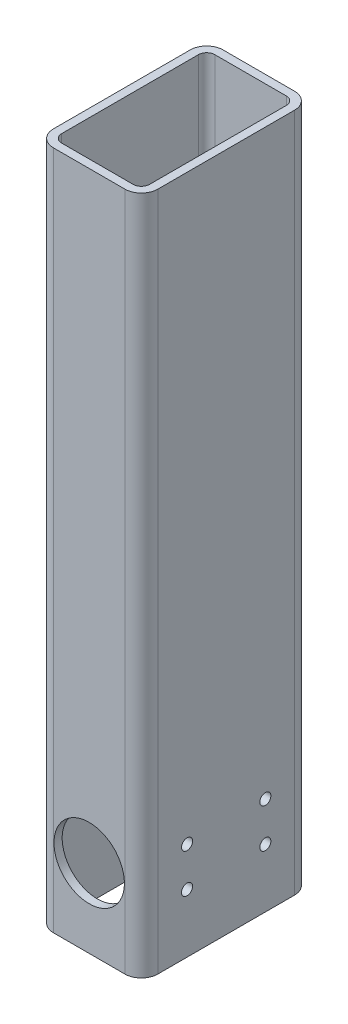
SolidWorks part; units mm, degrees
material "1.0037 (S235JR)"
ref_plane "E_Rechts" through (0, 0, 0) normal (0, 0, 1) x (1, 0, 0)
ref_plane "E_Oben" through (0, 0, 0) normal (0, 1, 0) x (1, 0, 0)
ref_plane "E_Vorne" through (0, 0, 0) normal (1, 0, 0) x (0, 0, -1)
sketch "Skizze1" plane through (0, 0, 0) normal (0, 1, 0) x (1, 0, 0)
  line L0 (-27.4, -58.7) -> (27.4, -58.7)
  line L1 (-33.7, -52.4) -> (-33.7, 52.4)
  line L2 (27.4, 58.7) -> (-27.4, 58.7)
  line L3 (33.7, 52.4) -> (33.7, -52.4)
  line L4 (-27.4, -65) -> (27.4, -65)
  line L5 (-40, -52.4) -> (-40, 52.4)
  line L6 (27.4, 65) -> (-27.4, 65)
  line L7 (40, 52.4) -> (40, -52.4)
  line L8 (-55, 0) -> (55, 0) construction
  line L9 (0, -55) -> (0, 55) construction
  arc A0 (40, 52.4) -> (27.4, 65) centre (27.4, 52.4) ccw
  arc A1 (27.4, -65) -> (40, -52.4) centre (27.4, -52.4) ccw
  arc A2 (-40, -52.4) -> (-27.4, -65) centre (-27.4, -52.4) ccw
  arc A3 (-27.4, 65) -> (-40, 52.4) centre (-27.4, 52.4) ccw
  arc A4 (-27.4, 58.7) -> (-33.7, 52.4) centre (-27.4, 52.4) ccw
  arc A5 (33.7, 52.4) -> (27.4, 58.7) centre (27.4, 52.4) ccw
  arc A6 (27.4, -58.7) -> (33.7, -52.4) centre (27.4, -52.4) ccw
  arc A7 (-33.7, -52.4) -> (-27.4, -58.7) centre (-27.4, -52.4) ccw
  dimension "D1" = 12.6
  dimension "D2" = 6.3
  dimension "D3" = 130
  dimension "D4" = 80
  dimension "D5" = 65
  dimension "D6" = 65
  dimension "D7" = 40
  dimension "D8" = 40
extrude "Aufsatz-Linear austragen1" add sketch "Skizze1" along normal blind 461 and the other way blind 60
sketch "Skizze3" plane through (0, 0, 0) normal (0, 0, 1) x (1, 0, 0)
  circle A0 centre (0, 0) radius 27
extrude "Schnitt-Linear austragen1" cut sketch "Skizze3" against normal through all both and the other way through all
hole_wizard "M10 Gewindebohrung2" positions "Skizze6" profile "Skizze7" tap size "M10" standard "DIN"
sketch "Skizze6" plane through (40, 0, 0) normal (1, 0, 0) x (0, 0, -1)
  line L0 (0, 44) -> (0, -44) construction
  line L1 (44, 0) -> (-44, 0) construction
  point P0 (-30, -15)
  dimension "D1" = 30
  dimension "D2" = 15
sketch "Skizze7" plane through (40, -15, 30) normal (0, 1, 0) x (0, 0, -1)
  line L0 (0, 0) -> (0, 30.0537)
  line L1 (0, 30.0537) -> (4.25, 27.5)
  line L2 (4.25, 27.5) -> (4.25, 0)
  line L5 (4.25, 0) -> (0, 0)
  line L10 (0, 30.0537) -> (-4.25, 27.5) construction
  line L11 (0, -6.35) -> (0, 107.95) construction
  dimension "Bohrerdurchmesser" = 8.5
  dimension "Bohrungstiefe" = 27.5
  dimension "Spitzenwinkel" = 118
cosmetic thread "Bohrungsgewinde7" parameters "D1"=20, "D2"=10
pattern_linear "Lineares Muster2" count 2 spacing 60 along (0, 0, -1) count 2 spacing 30 along (0, 1, 0) of "M10 Gewindebohrung2"
cosmetic thread "Bohrungsgewinde8" parameters "D1"=20, "D2"=10
cosmetic thread "Bohrungsgewinde9" parameters "D1"=20, "D2"=10
cosmetic thread "Bohrungsgewinde10" parameters "D1"=20, "D2"=10
